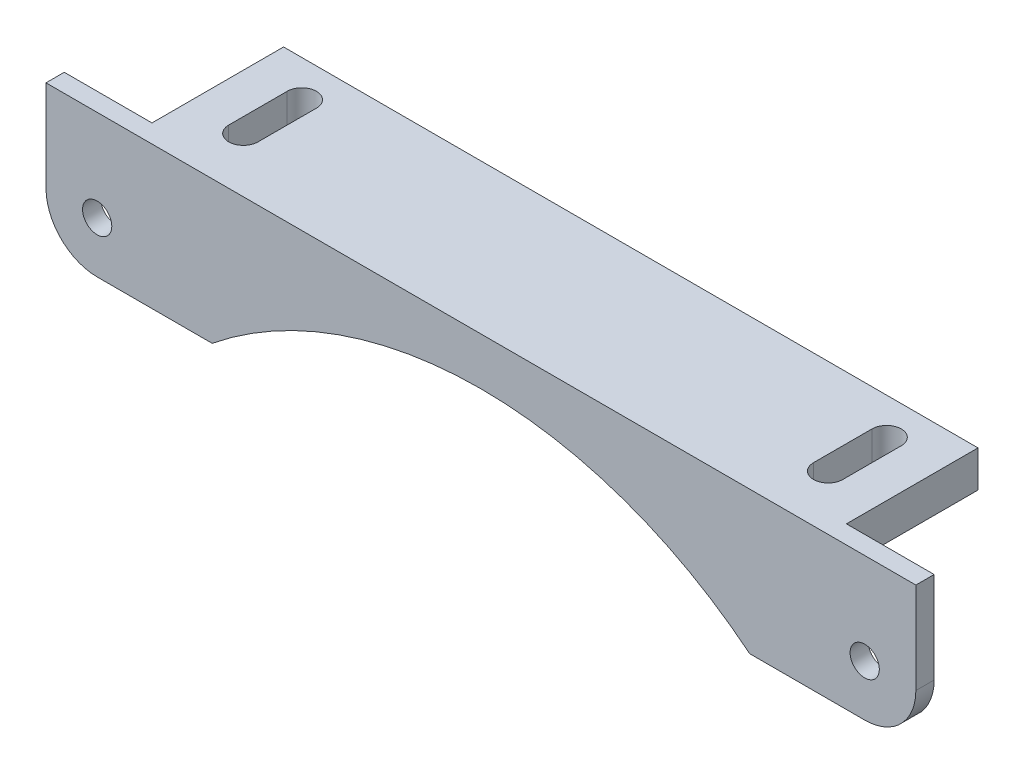
SolidWorks part; units mm, degrees
ref_plane "Front Plane" through (0, 0, 0) normal (0, 0, 1) x (1, 0, 0)
ref_plane "Top Plane" through (0, 0, 0) normal (0, 1, 0) x (1, 0, 0)
ref_plane "Right Plane" through (0, 0, 0) normal (1, 0, 0) x (0, 0, -1)
sketch "Sketch1" plane through (0, 0, 0) normal (0, 1, 0) x (1, 0, 0)
  line L0 (40, 0) -> (-40, 0) construction
  line L1 (-40, 4) -> (-40, -4) construction
  line L2 (-38, 4) -> (-38, -4)
  line L3 (-42, 4) -> (-42, -4)
  line L4 (40, 4) -> (40, -4) construction
  line L5 (42, 4) -> (42, -4)
  line L6 (38, 4) -> (38, -4)
  line L8 (47.5, -9) -> (-47.5, -9)
  line L9 (47.5, -9) -> (47.5, 9)
  line L10 (47.5, 9) -> (-47.5, 9)
  line L11 (-47.5, -9) -> (-47.5, 9)
  line L12 (47.5, -9) -> (-47.5, 9) construction
  line L13 (47.5, 9) -> (-47.5, -9) construction
  arc A0 (-38, 4) -> (-42, 4) centre (-40, 4) ccw
  arc A1 (-42, -4) -> (-38, -4) centre (-40, -4) ccw
  arc A2 (42, 4) -> (38, 4) centre (40, 4) ccw
  arc A3 (38, -4) -> (42, -4) centre (40, -4) ccw
  point P4 (0, 0)
  point P7 (-40, 0)
  point P14 (40, 0)
  point P19 (0, 0)
  dimension "D2" = 2
  dimension "D3" = 8
  dimension "D1" = 80
  dimension "D4" = 18
  dimension "D5" = 95
extrude "Boss-Extrude1" add sketch "Sketch1" along normal blind 5
sketch "Sketch2" plane through (0, 0, 9) normal (0, 0, 1) x (1, 0, 0)
  line L0 (0, -14.5) -> (52.5, -14.5) construction
  line L1 (60, -120) -> (-60, -120) construction
  line L2 (60, -120) -> (60, 0) construction
  line L3 (60, 0) -> (-60, 0) construction
  line L4 (-60, -120) -> (-60, 0) construction
  line L5 (60, -120) -> (-60, 0) construction
  line L6 (60, 0) -> (-60, -120) construction
  line L7 (52.5, -112.5) -> (-52.5, -112.5) construction
  line L8 (52.5, -112.5) -> (52.5, -7.5) construction
  line L9 (52.5, -7.5) -> (-52.5, -7.5) construction
  line L10 (-52.5, -112.5) -> (-52.5, -7.5) construction
  line L11 (52.5, -112.5) -> (-52.5, -7.5) construction
  line L12 (52.5, -7.5) -> (-52.5, -112.5) construction
  line L13 (-47.5, 0) -> (47.5, 0) construction
  line L14 (0, -120) -> (0, 0) construction
  line L15 (-52.5, -14.5) -> (0, -14.5) construction
  line L16 (-59.5, -7.5) -> (-59.5, 5)
  line L17 (-59.5, 5) -> (-47.5, 5)
  line L18 (59.5, 5) -> (59.5, -7.5)
  line L19 (59.5, 5) -> (47.5, 5)
  line L20 (-52.5, -14.5) -> (-36.7696, -14.5)
  line L21 (36.7696, -14.5) -> (52.5, -14.5)
  circle A0 centre (-52.5, -7.5) radius 2
  circle A1 centre (52.5, -7.5) radius 2
  arc A2 (-59.5, -7.5) -> (-52.5, -14.5) centre (-52.5, -7.5) ccw
  arc A3 (52.5, -14.5) -> (59.5, -7.5) centre (52.5, -7.5) ccw
  circle A4 centre (0, -60) radius 58.5 construction
  arc A5 (-36.7696, -14.5) -> (36.7696, -14.5) centre (0, -60) cw
  point P0 (0, -60)
  point P7 (0, -60)
  point P16 (0, -60)
  line M12 (-47.5, 0) -> (47.5, 0)
  line M13 (47.5, 0) -> (47.5, 5)
  line M14 (47.5, 5) -> (-47.5, 5)
  line M15 (-47.5, 5) -> (-47.5, 0)
  dimension "D4" = 4
  dimension "D5" = 7
  dimension "D6" = 117
  dimension "D1" = 105
  dimension "D2" = 120
  dimension "D3" = 120
extrude "Boss-Extrude2" add sketch "Sketch2" along normal blind 2.5 contours L20 A5 L21 A3 L18 L19 L17 L16 A2 A0 A1 M13 M12 M15 | M15 M12 M13 M14
